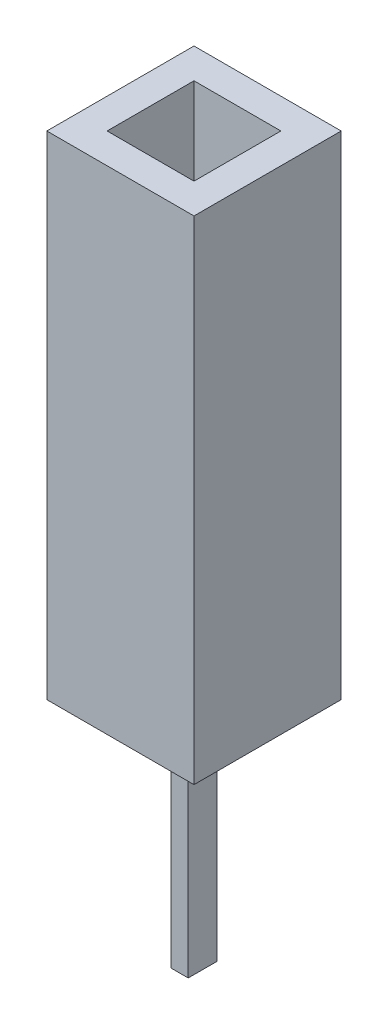
SolidWorks part; units mm, degrees
ref_plane "前视基准面" through (0, 0, 0) normal (0, 0, 1) x (1, 0, 0)
ref_plane "上视基准面" through (0, 0, 0) normal (0, 1, 0) x (1, 0, 0)
ref_plane "右视基准面" through (0, 0, 0) normal (1, 0, 0) x (0, 0, -1)
sketch "草图2" plane through (0, 0, 0) normal (0, 1, 0) x (1, 0, 0)
  line L0 (-5.8527, 0) -> (4.5687, 0) construction
  line L1 (-1.27, 1.27) -> (1.27, 1.27)
  line L2 (-1.27, 1.27) -> (-1.27, -1.27)
  line L3 (-1.27, -1.27) -> (1.27, -1.27)
  line L4 (1.27, 1.27) -> (1.27, -1.27)
  line L5 (0, 4.3929) -> (0, -2.7297) construction
  dimension "D1" = 2.54
  dimension "D2" = 2.54
extrude "拉伸1" add sketch "草图2" along normal blind 8.5
sketch "草图3" plane through (0, 0, 0) normal (0, -1, 0) x (1, 0, 0)
  line L0 (0, -0.6132) -> (0, 0.427) construction
  line L1 (0.15, 0.25) -> (-0.15, 0.25)
  line L2 (0.15, 0.25) -> (0.15, -0.25)
  line L3 (0.15, -0.25) -> (-0.15, -0.25)
  line L4 (-0.15, 0.25) -> (-0.15, -0.25)
  line L5 (0.3693, 0) -> (-0.358, 0) construction
  dimension "D1" = 0.5
  dimension "D2" = 0.3
extrude "拉伸2" add sketch "草图3" along normal blind 3.96
sketch "草图4" plane through (0, 8.5, 0) normal (0, 1, 0) x (-1, 0, 0)
  line L0 (0, 1.8247) -> (0, -1.4959) construction
  line L1 (-0.75, -0.75) -> (0.75, -0.75)
  line L2 (-0.75, -0.75) -> (-0.75, 0.75)
  line L3 (-0.75, 0.75) -> (0.75, 0.75)
  line L4 (0.75, -0.75) -> (0.75, 0.75)
  line L5 (-1.6234, 0) -> (1.5161, 0) construction
  dimension "D1" = 1.5
  dimension "D2" = 1.5
extrude "切除-拉伸1" cut sketch "草图4" against normal blind 7
